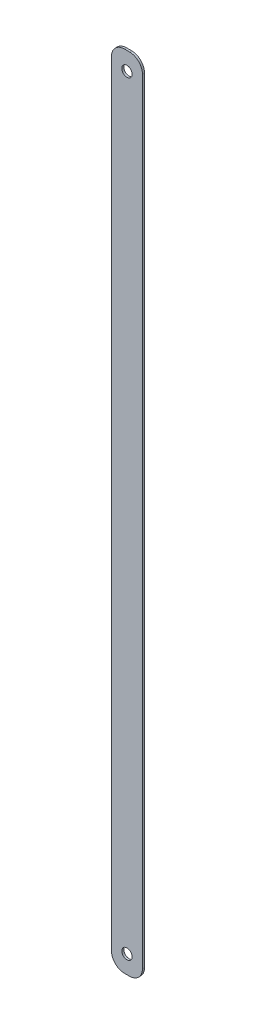
SolidWorks part; units mm, degrees
ref_plane "Alzado" through (0, 0, 0) normal (0, 0, 1) x (1, 0, 0)
ref_plane "Planta" through (0, 0, 0) normal (0, 1, 0) x (1, 0, 0)
ref_plane "Vista lateral" through (0, 0, 0) normal (1, 0, 0) x (0, 0, -1)
sketch "Croquis1" plane through (0, 0, 0) normal (0, 0, 1) x (1, 0, 0)
  line L0 (-6, 148) -> (6, 148) construction
  line L1 (-1, -155) -> (1, -155)
  line L2 (-6, -150) -> (-6, 150)
  line L3 (-1, 155) -> (1, 155)
  line L4 (6, -150) -> (6, 150)
  line L5 (-6, -155) -> (6, 155) construction
  line L6 (-6, 155) -> (6, -155) construction
  line L7 (-6, 0) -> (6, 0) construction
  arc A0 (1, -155) -> (6, -150) centre (1, -150) ccw
  arc A1 (-1, -155) -> (-6, -150) centre (-1, -150) cw
  arc A2 (1, 155) -> (6, 150) centre (1, 150) cw
  arc A3 (-6, 150) -> (-1, 155) centre (-1, 150) cw
  circle A4 centre (0, 148) radius 2
  circle A5 centre (0, -148) radius 2
  point P0 (0, 0)
  dimension "D3" = 5
  dimension "D5" = 4
  dimension "D1" = 310
  dimension "D2" = 12
  dimension "D4" = 7
extrude "Saliente-Extruir1" add sketch "Croquis1" along normal mid plane 0.8
